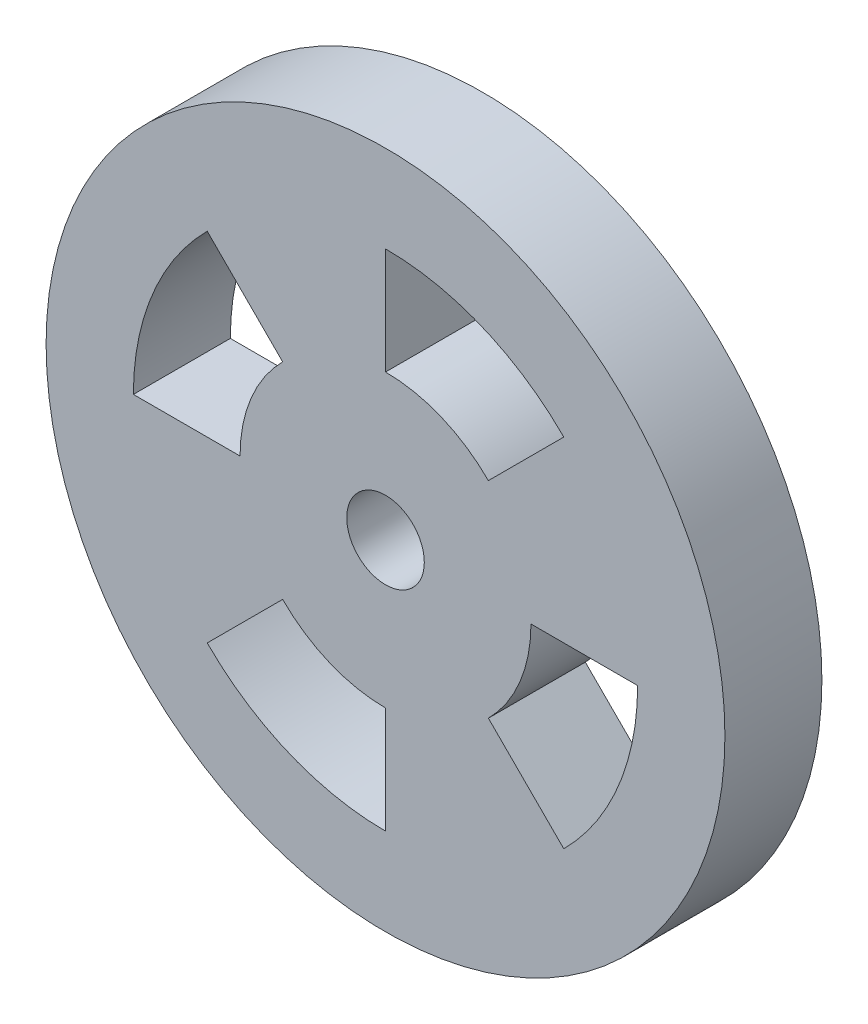
SolidWorks part; units mm, degrees
ref_plane "Front Plane" through (0, 0, 0) normal (0, 0, 1) x (1, 0, 0)
ref_plane "Top Plane" through (0, 0, 0) normal (0, 1, 0) x (1, 0, 0)
ref_plane "Right Plane" through (0, 0, 0) normal (1, 0, 0) x (0, 0, -1)
sketch "Sketch2" plane through (0, 0, 0) normal (0, 0, 1) x (1, 0, 0)
  circle A0 centre (0, 0) radius 3.5
extrude "Boss-Extrude1" add sketch "Sketch2" along normal blind 1
sketch "Sketch4" plane through (0, 0, 1) normal (0, 0, 1) x (1, 0, 0)
  circle A0 centre (0, 0) radius 0.4
extrude "Cut-Extrude2" cut sketch "Sketch4" against normal through all
sketch "Sketch5" plane through (0, 0, 1) normal (0, 0, 1) x (1, 0, 0)
  line L0 (0, 4.2445) -> (0, -4.196)
  line L3 (-4.7065, 0) -> (5.8321, 0)
  line L13 (0.55, -2.5) -> (0.25, -2.5)
  line L14 (0.55, -1.5) -> (0.55, -2.5)
  line L15 (0.55, -1.5) -> (0.25, -1.5)
  line L16 (0.25, -1.5) -> (0.25, -2.5)
  line L17 (-1.0607, -1.0607) -> (-1.8385, -1.8385)
  line L18 (0, 0) -> (2.4749, -2.4749)
  line L20 (0, 0) -> (1.3394, -3.2336)
  circle A0 centre (0, 0) radius 3.5 construction
  circle A3 centre (0, 0) radius 1.5
  circle A4 centre (0, 0) radius 2.6
extrude "Cut-Extrude3" cut sketch "Sketch5" against normal through all from surface at 0
pattern_circular "CirPattern1" count 4 over 360 about axis through (0, 0, 1) along (0, 0, 1) of "Cut-Extrude3"
